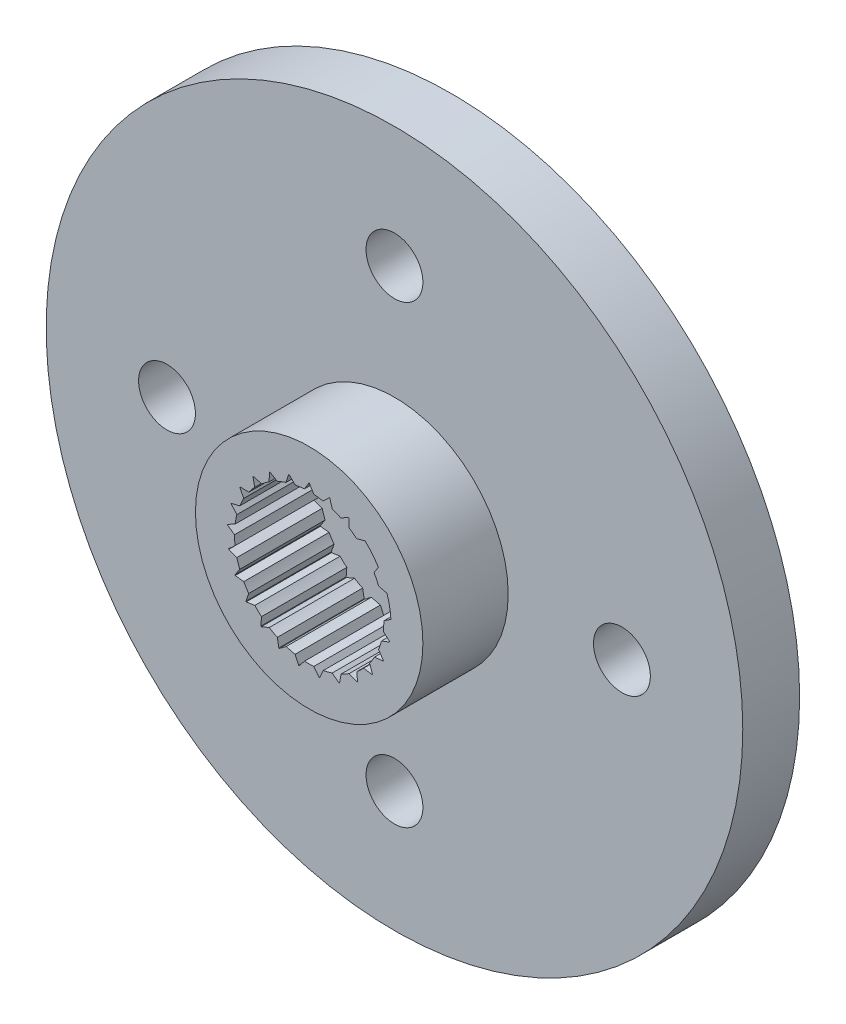
SolidWorks part; units mm, degrees
ref_plane "Front Plane" through (0, 0, 0) normal (0, 0, 1) x (1, 0, 0)
ref_plane "Top Plane" through (0, 0, 0) normal (0, 1, 0) x (1, 0, 0)
ref_plane "Right Plane" through (0, 0, 0) normal (1, 0, 0) x (0, 0, -1)
sketch "Sketch1" plane through (0, 0, 0) normal (0, 0, 1) x (1, 0, 0)
  circle A0 centre (0, 0) radius 12.25
extrude "Boss-Extrude1" add sketch "Sketch1" along normal blind 2
sketch "Sketch2" plane through (0, 0, 2) normal (0, 0, 1) x (1, 0, 0)
  line L0 (-14.3323, 0) -> (13.8773, 0) construction
  line L1 (0, 13.8058) -> (0, -14.7886) construction
  circle A0 centre (-8, 0) radius 1
  circle A1 centre (0, 8) radius 1
  circle A2 centre (8, 0) radius 1
  circle A3 centre (0, -8) radius 1
  dimension "D2" = 4
  dimension "D3" = 2
  dimension "D1" = 8
  dimension "D4" = 8
  dimension "D5" = 8
extrude "Cut-Extrude1" cut sketch "Sketch2" against normal up to vertex (2 mm away) up to point (0, 0, 0)
sketch "Sketch3" plane through (0, 0, 2) normal (0, 0, 1) x (1, 0, 0)
  line L0 (-8, 0) -> (8, 0) construction
  line L1 (0, 8) -> (0, -8) construction
  circle A0 centre (0, 0) radius 1.35
extrude "Cut-Extrude2" cut sketch "Sketch3" against normal blind 4
sketch "Sketch4" plane through (0, 0, 2) normal (0, 0, 1) x (1, 0, 0)
  circle A0 centre (0, 0) radius 2.88
  circle A1 centre (0, 0) radius 4
extrude "Boss-Extrude2" add sketch "Sketch4" along normal blind 3
sketch "Sketch5" plane through (0, 0, 5) normal (0, 0, 1) x (1, 0, 0)
  line L0 (-0.3609, -2.8697) -> (-0.1618, -2.6206)
  line L2 (0.1625, -2.6206) -> (0.3617, -2.8696)
  line L3 (-0.3609, -2.8697) -> (0.3617, -2.8696) construction
  line L4 (0.0004, -2.8697) -> (0.0004, -2.6256) construction
  line L6 (-0.4943, -2.5787) -> (-0.3633, -2.8694)
  line L7 (-1.0633, -2.6898) -> (-0.8084, -2.4981)
  line L9 (-1.12, -2.3747) -> (-1.0655, -2.6889)
  line L10 (-1.6988, -2.3409) -> (-1.4042, -2.2185)
  line L12 (-1.6754, -2.0216) -> (-1.7007, -2.3394)
  line L13 (-2.2276, -1.8448) -> (-1.9118, -1.7996)
  line L15 (-2.1255, -1.5414) -> (-2.2291, -1.843)
  line L16 (-2.6164, -1.2329) -> (-2.2993, -1.2676)
  line L18 (-2.4421, -0.9644) -> (-2.6174, -1.2307)
  line L19 (-2.8408, -0.5435) -> (-2.5423, -0.656)
  line L21 (-2.6052, -0.3267) -> (-2.8412, -0.5411)
  line L22 (-2.8867, 0.18) -> (-2.6256, -0.0031)
  line L24 (-2.6046, 0.3314) -> (-2.8866, 0.1825)
  line L25 (-2.7512, 0.8923) -> (-2.5439, 0.6499)
  line L27 (-2.4404, 0.9687) -> (-2.7505, 0.8946)
  line L28 (-2.4429, 1.5484) -> (-2.3023, 1.2622)
  line L30 (-2.1228, 1.5452) -> (-2.4416, 1.5505)
  line L31 (-1.9811, 2.1073) -> (-1.9161, 1.7951)
  line L33 (-1.6718, 2.0246) -> (-1.9793, 2.109)
  line L34 (-1.3948, 2.5338) -> (-1.4095, 2.2152)
  line L36 (-1.1158, 2.3767) -> (-1.3926, 2.535)
  line L37 (-0.7208, 2.8011) -> (-0.8143, 2.4961)
  line L39 (-0.4897, 2.5795) -> (-0.7185, 2.8017)
  line L40 (-0.0016, 2.8923) -> (-0.168, 2.6202)
  line L42 (0.1672, 2.6203) -> (0.0008, 2.8923)
  line L43 (0.7178, 2.8018) -> (0.4889, 2.5797)
  line L45 (0.8136, 2.4964) -> (0.7201, 2.8012)
  line L46 (1.392, 2.5353) -> (1.1151, 2.377)
  line L48 (1.4088, 2.2156) -> (1.3941, 2.5341)
  line L49 (1.9788, 2.1095) -> (1.6712, 2.025)
  line L57 (2.5437, 0.6507) -> (2.751, 0.893)
  line L58 (2.8865, 0.1832) -> (2.6045, 0.3322)
  line L60 (2.6256, -0.0023) -> (2.8867, 0.1808)
  line L61 (2.8414, -0.5404) -> (2.6053, -0.326)
  line L63 (2.5425, -0.6552) -> (2.8409, -0.5428)
  line L64 (2.6177, -1.2301) -> (2.4424, -0.9637)
  line L66 (2.2997, -1.2669) -> (2.6167, -1.2323)
  line L67 (2.2296, -1.8424) -> (2.126, -1.5408)
  line L69 (1.9124, -1.7991) -> (2.228, -1.8443)
  line L70 (1.7013, -2.339) -> (1.676, -2.0211)
  line L72 (1.4049, -2.2181) -> (1.6994, -2.3404)
  line L73 (1.0662, -2.6886) -> (1.1207, -2.3744)
  line L75 (0.8091, -2.4978) -> (1.0639, -2.6895)
  line L76 (0.3641, -2.8693) -> (0.495, -2.5785)
  line L77 (2.282, 1.2985) -> (2.4425, 1.5491)
  line L78 (2.4412, 1.5511) -> (2.4425, 1.5491)
  line L79 (2.4395, 1.5511) -> (2.1223, 1.5458) [skipped]
  line L80 (1.9155, 1.7952) -> (1.9801, 2.1058) [skipped]
  line L81 (2.7486, 0.8957) -> (2.4401, 0.9694) [skipped]
  line L82 (1.9805, 2.1078) -> (1.9156, 1.7956)
  line L83 (2.4412, 1.5511) -> (2.1223, 1.5458)
  line L84 (2.751, 0.893) -> (2.441, 0.9671)
  line L85 (2.302, 1.2628) -> (2.4425, 1.5491) [skipped]
  arc A2 (-0.3609, -2.8697) -> (0.3617, -2.8696) centre (0, 0) ccw
  arc A3 (-1.0633, -2.6898) -> (-0.3633, -2.8694) centre (0, 0) ccw
  arc A4 (-1.6988, -2.3409) -> (-1.0655, -2.6889) centre (0, 0) ccw
  arc A5 (-2.2276, -1.8448) -> (-1.7007, -2.3394) centre (0, 0) ccw
  arc A6 (-2.6164, -1.2329) -> (-2.2291, -1.843) centre (0, 0) ccw
  arc A7 (-2.8408, -0.5435) -> (-2.6174, -1.2307) centre (0, 0) ccw
  arc A8 (-2.8867, 0.18) -> (-2.8412, -0.5411) centre (0, 0) ccw
  arc A9 (-2.7512, 0.8923) -> (-2.8866, 0.1825) centre (0, 0) ccw
  arc A10 (-2.4429, 1.5484) -> (-2.7505, 0.8946) centre (0, 0) ccw
  arc A11 (-1.9811, 2.1073) -> (-2.4416, 1.5505) centre (0, 0) ccw
  arc A12 (-1.3948, 2.5338) -> (-1.9793, 2.109) centre (0, 0) ccw
  arc A13 (-0.7208, 2.8011) -> (-1.3926, 2.535) centre (0, 0) ccw
  arc A14 (-0.0016, 2.8923) -> (-0.7185, 2.8017) centre (0, 0) ccw
  arc A15 (0.7178, 2.8018) -> (0.0008, 2.8923) centre (0, 0) ccw
  arc A16 (1.392, 2.5353) -> (0.7201, 2.8012) centre (0, 0) ccw
  arc A17 (1.9788, 2.1095) -> (1.3941, 2.5341) centre (0, 0) ccw
  arc A18 (2.4412, 1.5511) -> (1.9805, 2.1078) centre (0, 0) ccw
  arc A19 (2.7503, 0.8953) -> (2.4425, 1.5491) centre (0, 0) ccw
  arc A20 (2.8865, 0.1832) -> (2.751, 0.893) centre (0, 0) ccw
  arc A21 (2.8414, -0.5404) -> (2.8867, 0.1808) centre (0, 0) ccw
  arc A22 (2.6177, -1.2301) -> (2.8409, -0.5428) centre (0, 0) ccw
  arc A23 (2.2296, -1.8424) -> (2.6167, -1.2323) centre (0, 0) ccw
  arc A24 (1.7013, -2.339) -> (2.228, -1.8443) centre (0, 0) ccw
  arc A25 (1.0662, -2.6886) -> (1.6994, -2.3404) centre (0, 0) ccw
  arc A26 (0.3641, -2.8693) -> (1.0639, -2.6895) centre (0, 0) ccw
  circle A27 centre (0, 0) radius 2.6256
  dimension "D1" = 25
  dimension "D2" = 62.898
  dimension "D4" = 62.898
sketch "Sketch6" plane through (0, 0, 0) normal (0, 0, -1) x (-1, 0, 0)
  circle A0 centre (0, 0) radius 2
extrude "Cut-Extrude3" cut sketch "Sketch6" against normal blind 1
extrude "Boss-Extrude4" add sketch "Sketch5" against normal up to surface (3 mm away)
sketch "Sketch7" plane through (0, 0, 0) normal (0, 0, -1) x (-1, 0, 0)
  line L0 (0, 8) -> (0, -8) construction
  line L1 (-8, 0) -> (8, 0) construction
